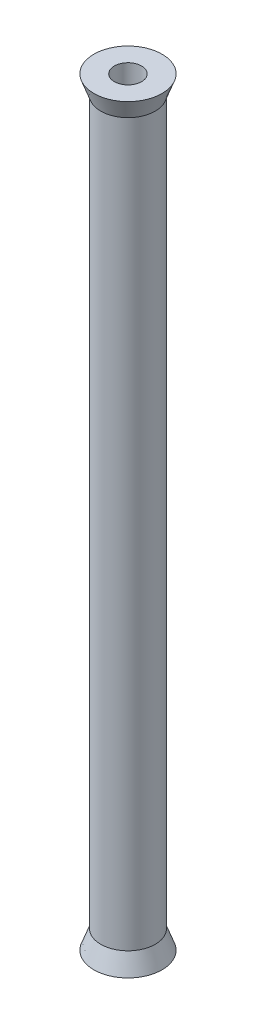
SolidWorks part; units mm, degrees
material "PET"
ref_plane "Front Plane" through (0, 0, 0) normal (0, 0, 1) x (1, 0, 0)
ref_plane "Top Plane" through (0, 0, 0) normal (0, 1, 0) x (1, 0, 0)
ref_plane "Right Plane" through (0, 0, 0) normal (1, 0, 0) x (0, 0, -1)
other "Configuration Table"
sketch "Sketch1" plane through (0, 0, 0) normal (0, 0, 1) x (1, 0, 0)
  line L0 (0, 0) -> (0, -50000) construction
  line L2 (2, -55.7) -> (5, -55.7)
  line L3 (2, 55.7) -> (5, 55.7)
  line L4 (4, -52.9525) -> (4, 52.9525)
  line L5 (2, 55.7) -> (2, -55.7)
  line L8 (5.5, 0) -> (-5.5, 0) construction
  line L9 (5, 55.7) -> (4, 52.9525)
  line L10 (5, -55.7) -> (4, -52.9525)
  point P4 (0, 0)
  dimension "Length" = 111.4
  dimension "D2" = 10
  dimension "D3" = 8
  dimension "ThreadDia" = 4
  dimension "D1" = 70
revolve "Revolve1" add sketch "Sketch1" angle 360 about L0
equation "\"D3@Sketch1\"= \"ThreadDia@Sketch1\" * 2"
equation "\"D2@Sketch1\"= \"ThreadDia@Sketch1\" * 2.5"
